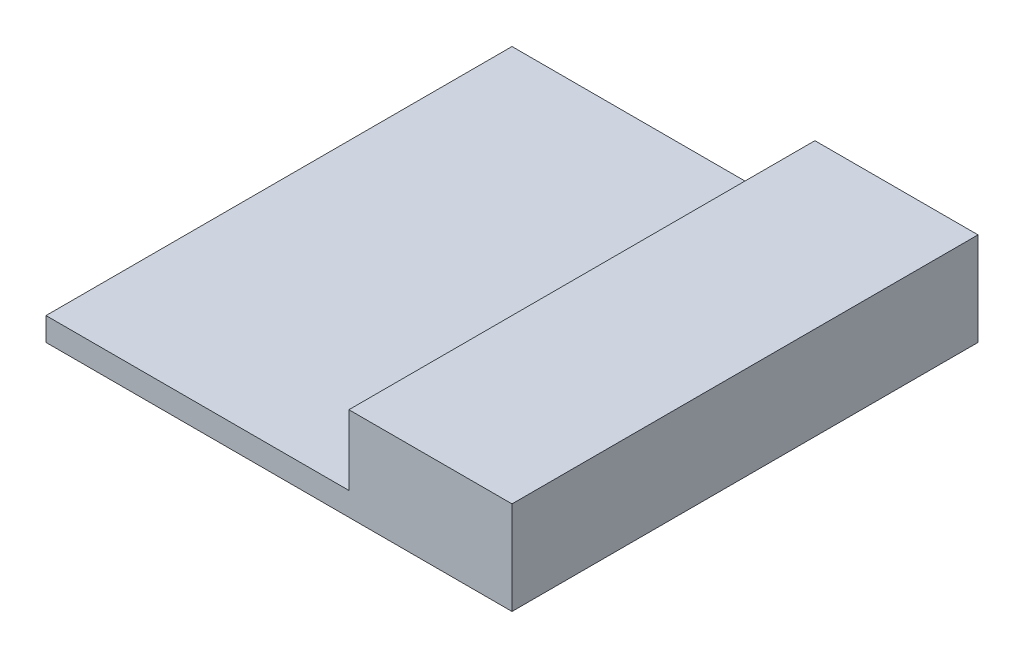
SolidWorks part; units mm, degrees
ref_plane "前视基准面" through (0, 0, 0) normal (0, 0, 1) x (1, 0, 0)
ref_plane "上视基准面" through (0, 0, 0) normal (0, 1, 0) x (1, 0, 0)
ref_plane "右视基准面" through (0, 0, 0) normal (1, 0, 0) x (0, 0, -1)
other "Configuration Table"
sketch "草图1" plane through (0, 0, 0) normal (0, 1, 0) x (1, 0, 0)
  line L1 (0, 0) -> (100, 0)
  line L2 (0, 0) -> (0, -100)
  line L3 (0, -100) -> (100, -100)
  line L4 (100, 0) -> (100, -100)
  dimension "D1" = 100
  dimension "D2" = 100
extrude "凸台-拉伸1" add sketch "草图1" along normal blind 5
sketch "草图2" plane through (0, 5, 0) normal (0, 1, 0) x (1, 0, 0)
  line L0 (0, -100) -> (100, -100) construction
  line L1 (100, 0) -> (65, 0)
  line L2 (100, 0) -> (100, -100)
  line L3 (100, -100) -> (65, -100)
  line L4 (65, 0) -> (65, -100)
  dimension "D1" = 35
extrude "凸台-拉伸2" add sketch "草图2" along normal blind 15
